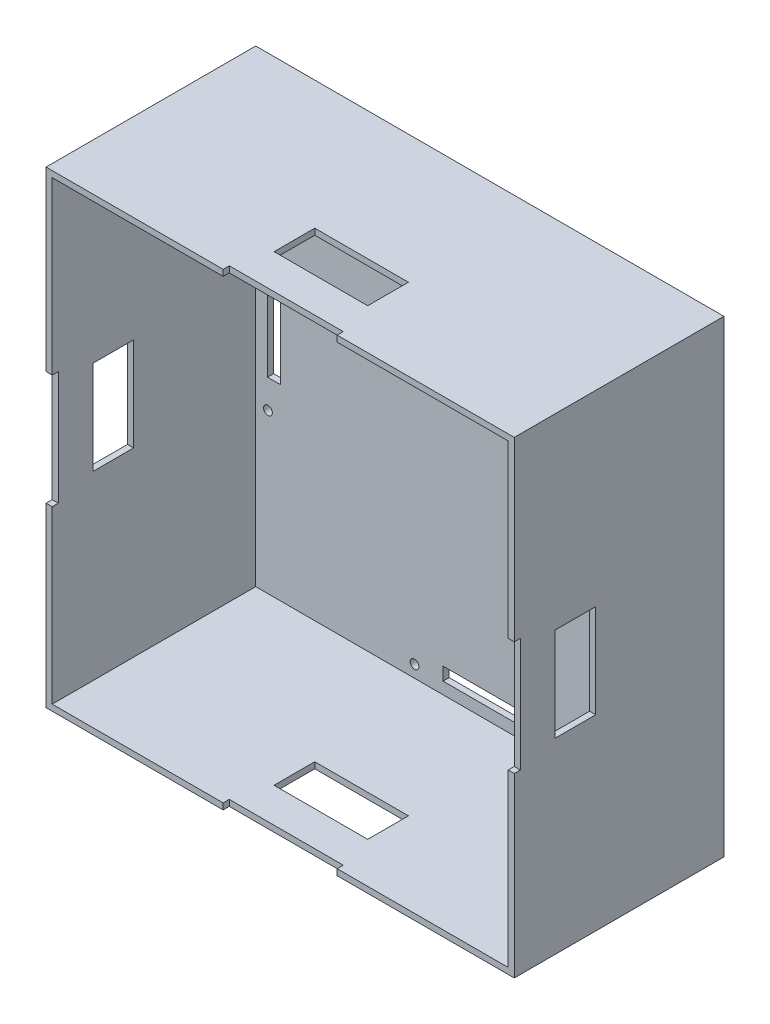
SolidWorks part; units mm, degrees
material "아크릴(내충격성)"
ref_plane "정면" through (0, 0, 0) normal (0, 0, 1) x (1, 0, 0)
ref_plane "윗면" through (0, 0, 0) normal (0, 1, 0) x (1, 0, 0)
ref_plane "우측면" through (0, 0, 0) normal (1, 0, 0) x (0, 0, -1)
sketch "스케치1" plane through (0, 0, 0) normal (0, 0, 1) x (1, 0, 0)
  line L1 (-115, 115) -> (115, 115)
  line L2 (-115, 115) -> (-115, -115)
  line L3 (-115, -115) -> (115, -115)
  line L4 (115, 115) -> (115, -115)
  line L5 (-115, 115) -> (115, -115) construction
  line L6 (-115, -115) -> (115, 115) construction
  point P0 (0, 0)
  dimension "D1" = 230
  dimension "D2" = 230
extrude "보스-돌출1" add sketch "스케치1" along normal blind 3 contours L1 L4 L3 L2
sketch "스케치3" plane through (0, 0, 3) normal (0, 0, 1) x (1, 0, 0)
  line L1 (-115, 115) -> (115, 115)
  line L2 (-115, 115) -> (-115, -115)
  line L3 (-115, -115) -> (115, -115)
  line L4 (115, 115) -> (115, -115)
  line L5 (-115, 115) -> (115, -115) construction
  line L6 (-115, -115) -> (115, 115) construction
  line L7 (-125, 125) -> (125, 125)
  line L8 (-125, 125) -> (-125, -125)
  line L9 (-125, -125) -> (125, -125)
  line L10 (125, 125) -> (125, -125)
  line L11 (-125, 125) -> (125, -125) construction
  line L12 (-125, -125) -> (125, 125) construction
  point P0 (0, 0)
  point P7 (0, 0)
  line M9 (-115, 115) -> (-115, -115)
  line M10 (-115, -115) -> (115, -115)
  line M11 (115, -115) -> (115, 115)
  line M12 (115, 115) -> (-115, 115)
extrude "보스-돌출3" add sketch "스케치3" along normal blind 100 contours M12 M9 M10 M11
sketch "스케치4" plane through (0, 0, 103) normal (0, 0, 1) x (1, 0, 0)
  line L1 (-110, 110) -> (110, 110)
  line L2 (-110, 110) -> (-110, -110)
  line L3 (-110, -110) -> (110, -110)
  line L4 (110, 110) -> (110, -110)
  line L5 (-110, 110) -> (110, -110) construction
  line L6 (-110, -110) -> (110, 110) construction
  point P0 (0, 0)
  dimension "D1" = 220
  dimension "D2" = 220
extrude "컷-돌출1" cut sketch "스케치4" against normal blind 100 contours L2 L3 L4 L1
sketch "스케치5" plane through (-115, 0, 0) normal (-1, 0, 0) x (0, 0, 1)
  text T0 "\r\n\r\n\r\nfront" font "Century Gothic" height 20
extrude "컷-돌출2" [suppressed] cut sketch "스케치5" against normal blind 1
ref_plane "평면1" through (0, 0, 150) normal (0, 0, -1) x (-1, 0, 0)
sketch "스케치6" plane through (-115, 0, 0) normal (-1, 0, 0) x (0, 0, 1)
  line L1 (63, 23) -> (83, 23)
  line L2 (63, 23) -> (63, -23)
  line L3 (63, -23) -> (83, -23)
  line L4 (83, 23) -> (83, -23)
  line L5 (63, 23) -> (83, -23) construction
  line L6 (63, -23) -> (83, 23) construction
  line L9 (103, 115) -> (103, -115) construction
  point P0 (73, 0)
  dimension "D1" = 46
  dimension "D2" = 0
  dimension "D3" = 20
  dimension "D4" = 20
extrude "컷-돌출3" cut sketch "스케치6" against normal through all
sketch "스케치7" plane through (0, 0, 0) normal (0, 1, 0) x (1, 0, 0)
  line L0 (0, 0) -> (0, -331.8175) construction
pattern_circular "원형 패턴1" count 2 every 90 about axis through (0, 0, 0) along (0, 0, 1) of "컷-돌출3"
sketch "스케치11" plane through (0, 0, 103) normal (0, 0, 1) x (1, 0, 0)
  line L0 (115, 115) -> (-115, 115) construction
  line L1 (-112, 112) -> (112, 112)
  line L2 (-112, 112) -> (-112, -112)
  line L3 (-112, -112) -> (112, -112)
  line L4 (112, 112) -> (112, -112)
  line L5 (-112, 112) -> (112, -112) construction
  line L6 (-112, -112) -> (112, 112) construction
  line L7 (115, -115) -> (115, 115) construction
  point P0 (0, 0)
  dimension "D1" = 3
  dimension "D2" = 3
extrude "컷-돌출5" cut sketch "스케치11" against normal blind 100
sketch "스케치12" [suppressed] plane through (0, 0, -5) normal (0, 0, -1) x (-1, 0, 0)
  line L0 (125, 125) -> (-125, 125) construction
  line L1 (-120, 120) -> (120, 120)
  line L2 (-120, 120) -> (-120, -120)
  line L3 (-120, -120) -> (120, -120)
  line L4 (120, 120) -> (120, -120)
  line L5 (-120, 120) -> (120, -120) construction
  line L6 (-120, -120) -> (120, 120) construction
  line L7 (-125, 125) -> (-125, -125) construction
  point P0 (0, 0)
  dimension "D1" = 5
  dimension "D2" = 5
extrude "컷-돌출6" [suppressed] cut sketch "스케치12" against normal blind 5 flip side to cut
sketch "스케치13" plane through (-115, 0, 0) normal (-1, 0, 0) x (0, 0, 1)
  line L0 (103, 115) -> (103, -115) construction
  line L1 (103, 28) -> (100, 28)
  line L2 (103, 28) -> (103, -28)
  line L3 (103, -28) -> (100, -28)
  line L4 (100, 28) -> (100, -28)
  point P6 (103, 0)
  dimension "D1" = 3
  dimension "D2" = 28
  dimension "D3" = 28
extrude "컷-돌출7" cut sketch "스케치13" against normal through all
sketch "스케치14" plane through (0, 0, 3) normal (0, 0, 1) x (1, 0, 0)
  line L2 (-112, 112) -> (-112, -112) construction
  line L3 (-112, 28) -> (-112, -28) construction
  line L4 (-106.2, -20) -> (-99.8, -20)
  line L5 (-106.2, -20) -> (-106.2, 20)
  line L6 (-106.2, 20) -> (-99.8, 20)
  line L7 (-99.8, -20) -> (-99.8, 20)
  line L8 (-20, 106.2) -> (-20, 99.8)
  line L21 (-20, 106.2) -> (20, 106.2)
  line L22 (20, 106.2) -> (20, 99.8)
  line L23 (-20, 99.8) -> (20, 99.8)
  line L24 (106.2, 20) -> (99.8, 20)
  line L25 (106.2, 20) -> (106.2, -20)
  line L26 (106.2, -20) -> (99.8, -20)
  line L27 (99.8, 20) -> (99.8, -20)
  line L28 (20, -106.2) -> (20, -99.8)
  line L29 (20, -106.2) -> (-20, -106.2)
  line L30 (-20, -106.2) -> (-20, -99.8)
  line L31 (20, -99.8) -> (-20, -99.8)
  circle A0 centre (-106, -34) radius 2.15
  circle A1 centre (-106, 34) radius 2.15
  circle A14 centre (-34, 106) radius 2.15
  circle A15 centre (34, 106) radius 2.15
  circle A16 centre (106, 34) radius 2.15
  circle A17 centre (106, -34) radius 2.15
  circle A18 centre (34, -106) radius 2.15
  circle A19 centre (-34, -106) radius 2.15
  point P39 (0, 0)
  dimension "D3" = 4.3
  dimension "D4" = 4.3
  dimension "D2" = 34
  dimension "D5" = 6
  dimension "D6" = 6
  dimension "D8" = 40
  dimension "D9" = 20
  dimension "D10" = 6.4
  dimension "D11" = 5.8
  dimension "D7" = 34
  dimension "D12" = 4
extrude "컷-돌출8" cut sketch "스케치14" against normal through all
sketch "스케치15" plane through (0, 0, 0) normal (0, 1, 0) x (1, 0, 0)
  line L0 (0, 18.1057) -> (0, -180.7958) construction
pattern_circular "원형 패턴2" count 2 over 90 about axis through (0, 0, -18.1057) along (0, 0, 1) of "컷-돌출7"
